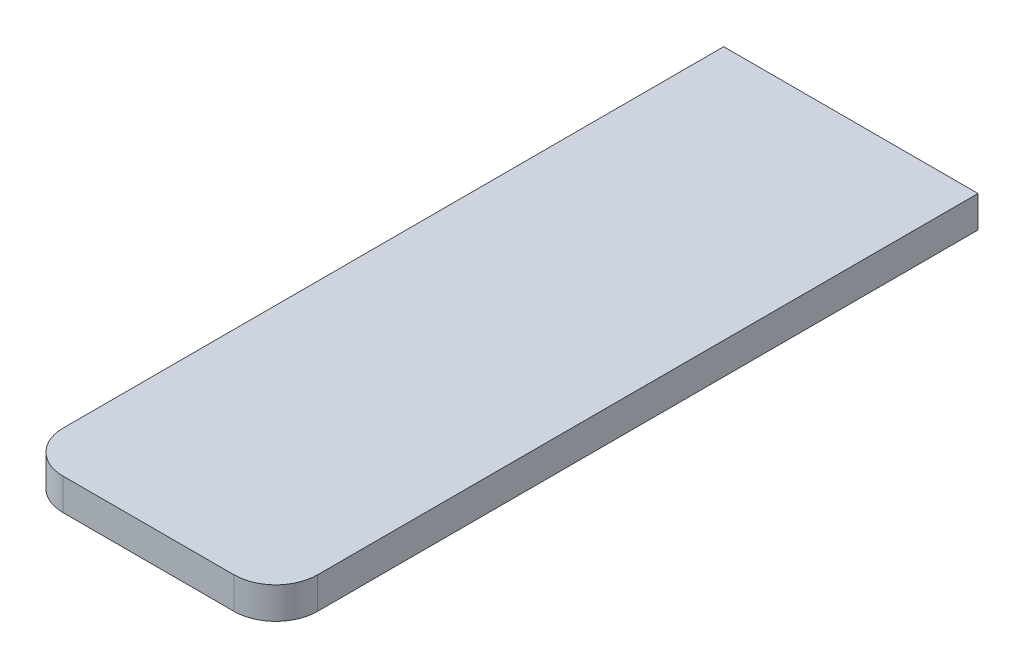
SolidWorks part; units mm, degrees
ref_plane "Front Plane" through (0, 0, 0) normal (0, 0, 1) x (1, 0, 0)
ref_plane "Top Plane" through (0, 0, 0) normal (0, 1, 0) x (1, 0, 0)
ref_plane "Right Plane" through (0, 0, 0) normal (1, 0, 0) x (0, 0, -1)
sketch "Sketch2" plane through (0, 0, 0) normal (0, 1, 0) x (1, 0, 0)
  line L1 (-12.05, -31.3) -> (12.05, -31.3)
  line L2 (-12.05, -31.3) -> (-12.05, 31.3)
  line L3 (-12.05, 31.3) -> (12.05, 31.3)
  line L4 (12.05, -31.3) -> (12.05, 31.3)
  line L5 (-12.05, -31.3) -> (12.05, 31.3) construction
  line L6 (-12.05, 31.3) -> (12.05, -31.3) construction
  point P0 (0, 0)
  dimension "D1" = 62.6
  dimension "D2" = 24.1
extrude "Boss-Extrude3" add sketch "Sketch2" along normal blind 3
ref_plane "Plane1" through (0, 3, 0) normal (0, 1, 0) x (1, 0, 0)
sketch "Sketch3" plane through (0, 3, 0) normal (0, 1, 0) x (1, 0, 0)
  line L1 (12.05, -31.3) -> (-12.05, -31.3)
  line L2 (12.05, -31.3) -> (12.05, -35.25)
  line L3 (12.05, -35.25) -> (-12.05, -35.25)
  line L4 (-12.05, -31.3) -> (-12.05, -35.25)
  dimension "D1" = 3.95
extrude "Boss-Extrude4" add sketch "Sketch3" against normal blind 3
fillet "Fillet1" radius 3.95 1 edges at (12.05, 1.5, 35.25)
fillet "Fillet2" radius 3.95 1 edges at (-12.05, 1.5, 35.25)
